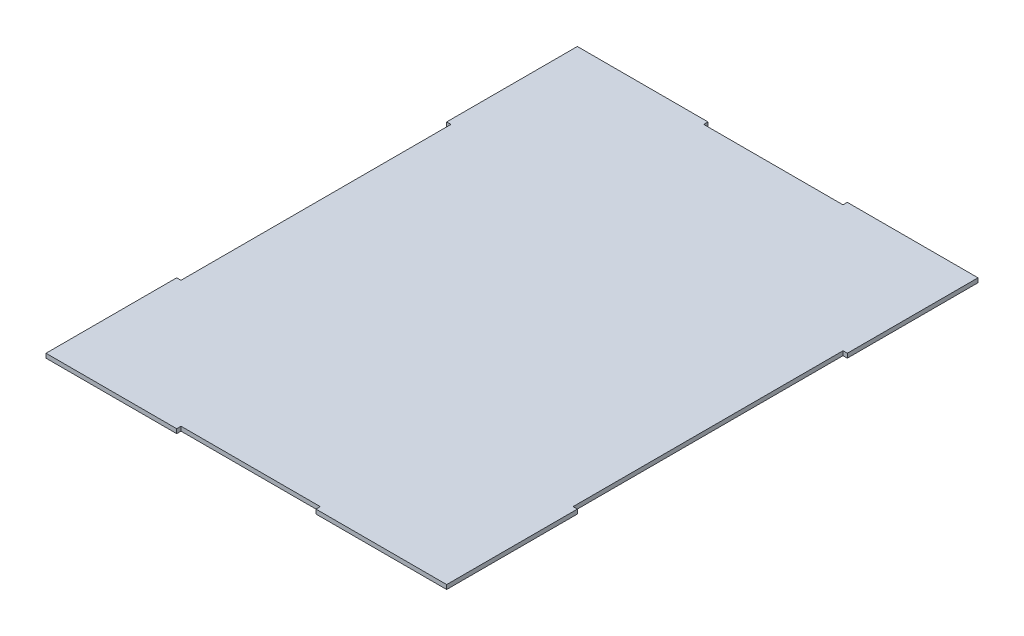
SolidWorks part; units mm, degrees
ref_plane "Alzado" through (0, 0, 0) normal (0, 0, 1) x (1, 0, 0)
ref_plane "Planta" through (0, 0, 0) normal (0, 1, 0) x (1, 0, 0)
ref_plane "Vista lateral" through (0, 0, 0) normal (1, 0, 0) x (0, 0, -1)
sketch "Croquis1" plane through (0, 0, 0) normal (0, 1, 0) x (1, 0, 0)
  line L0 (-53.3, 200) -> (53.3, 200)
  line L1 (-53.3, 200) -> (53.3, 200) construction
  line L2 (-150, 103.3) -> (-150, -103.3) construction
  line L4 (150, 103.3) -> (150, -103.3) construction
  line L7 (-153.3, 203.3) -> (-53.3, 203.3)
  line L8 (-53.3, 200) -> (-53.3, 203.3)
  line L10 (53.3, 200) -> (53.3, 203.3)
  line L11 (53.3, 203.3) -> (150, 203.3)
  line L13 (-150, 103.3) -> (-150, -103.3)
  line L16 (-150, 103.3) -> (-153.3, 103.3)
  line L17 (-153.3, 203.3) -> (-153.3, 103.3)
  line L20 (-150, -103.3) -> (-153.3, -103.3)
  line L21 (-153.3, -200) -> (-153.3, -103.3)
  line L22 (-150, 103.3) -> (-150, -103.3)
  line L23 (-150, 200) -> (-150, 203.3) construction
  line L24 (-150, 200) -> (-153.3, 200) construction
  line L25 (153.3, -103.3) -> (153.3, -200)
  line L26 (150, -200) -> (153.3, -200) construction
  line L27 (153.3, -103.3) -> (150, -103.3)
  line L28 (150, -103.3) -> (150, 103.3)
  line L29 (150, 103.3) -> (153.3, 103.3)
  line L30 (153.3, 103.3) -> (153.3, 203.3)
  line L31 (153.3, 203.3) -> (150, 203.3)
  line L32 (150, 200) -> (150, 203.3) construction
  line L33 (150, 200) -> (153.3, 200) construction
  line L39 (150, -200) -> (150, -203.3) construction
  line L41 (-53.3, -200) -> (53.3, -200)
  line L43 (-153.3, -200) -> (-153.3, -203.3)
  line L44 (-153.3, -203.3) -> (-53.3, -203.3)
  line L45 (-53.3, -200) -> (-53.3, -203.3)
  line L46 (153.3, -200) -> (150, -200)
  line L47 (153.3, -200) -> (153.3, -203.3)
  line L48 (153.3, -203.3) -> (53.3, -203.3)
  line L49 (53.3, -200) -> (53.3, -203.3)
  line L50 (-53.3, -200) -> (53.3, -200) construction
  line L51 (-150, 200) -> (150, 200) construction
  line L52 (-150, 200) -> (-150, -200) construction
  line L53 (-53.3, -200) -> (150, -200) construction
  line L54 (150, 200) -> (150, -200) construction
  line L55 (-150, -200) -> (-53.3, -200) construction
  line L56 (-153.3, -200) -> (-150, -200) construction
  line L57 (-150, -200) -> (-150, -203.3) construction
  point P4 (0, 200)
  point P5 (-150, 0)
  dimension "D1" = 300
  dimension "D2" = 400
  dimension "D3" = 3.3
  dimension "D4" = 100
  dimension "D5" = 100
  dimension "D6" = 100
  dimension "D7" = 100
extrude "Saliente-Extruir1" add sketch "Croquis1" along normal blind 3.3
